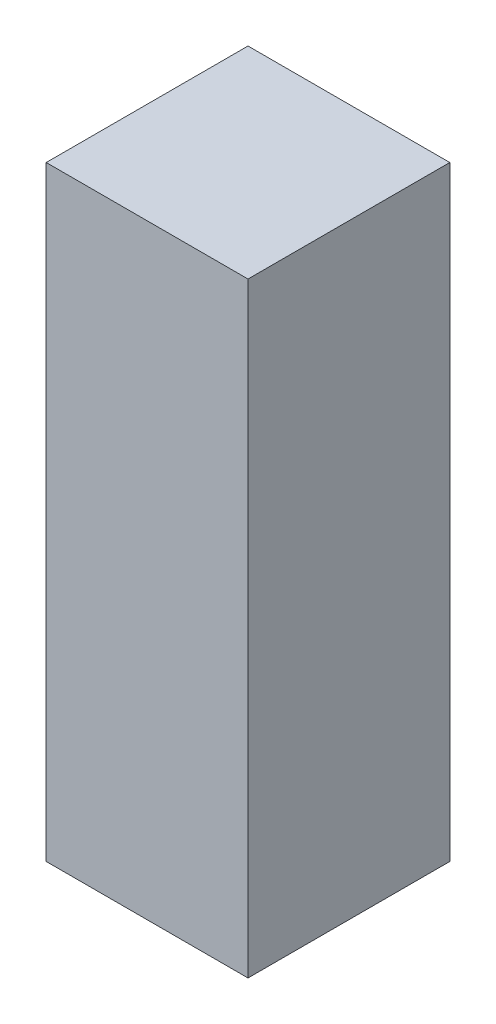
SolidWorks part; units mm, degrees
material "Aleación 1060"
ref_plane "Alzado" through (0, 0, 0) normal (0, 0, 1) x (1, 0, 0)
ref_plane "Planta" through (0, 0, 0) normal (0, 1, 0) x (1, 0, 0)
ref_plane "Vista lateral" through (0, 0, 0) normal (1, 0, 0) x (0, 0, -1)
sketch "Croquis1" plane through (0, 0, 0) normal (0, 0, 1) x (1, 0, 0)
  line L1 (-2.5, -7.5) -> (2.5, -7.5)
  line L2 (-2.5, -7.5) -> (-2.5, 7.5)
  line L3 (-2.5, 7.5) -> (2.5, 7.5)
  line L4 (2.5, -7.5) -> (2.5, 7.5)
  line L5 (-2.5, -7.5) -> (2.5, 7.5) construction
  line L6 (-2.5, 7.5) -> (2.5, -7.5) construction
  point P0 (0, 0)
  dimension "D1" = 5
  dimension "D2" = 15
extrude "Saliente-Extruir1" add sketch "Croquis1" along normal blind 5
